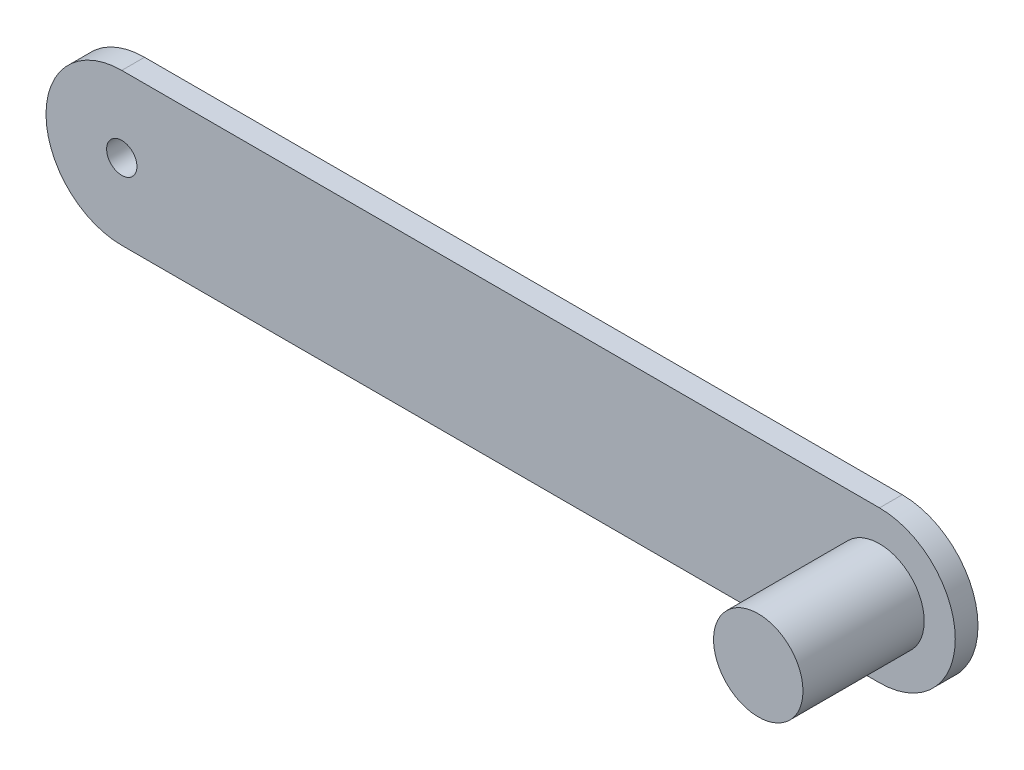
SolidWorks part; units mm, degrees
ref_plane "Front Plane" through (0, 0, 0) normal (0, 0, 1) x (1, 0, 0)
ref_plane "Top Plane" through (0, 0, 0) normal (0, 1, 0) x (1, 0, 0)
ref_plane "Right Plane" through (0, 0, 0) normal (1, 0, 0) x (0, 0, -1)
sketch "Sketch1" plane through (0, 0, 0) normal (0, 0, 1) x (1, 0, 0)
  line L0 (0, 5) -> (50, 5)
  line L6 (0, -5) -> (50, -5)
  arc A2 (0, 5) -> (0, -5) centre (0, 0) ccw
  arc A3 (50, -5) -> (50, 5) centre (50, 0) ccw
  dimension "D1" = 10
  dimension "D2" = 50
extrude "Boss-Extrude4" add sketch "Sketch1" along normal blind 1.5
sketch "Sketch4" plane through (0, 0, 1.5) normal (0, 0, 1) x (1, 0, 0)
  circle A0 centre (0, 0) radius 1
  dimension "D1" = 2
extrude "Cut-Extrude1" cut sketch "Sketch4" against normal through all
sketch "Sketch5" plane through (0, 0, 1.5) normal (0, 0, 1) x (1, 0, 0)
  circle A0 centre (50, 0) radius 2.95
  circle A1 centre (0, 0) radius 1 construction
  dimension "D1" = 5.9
  dimension "D2" = 50
extrude "Boss-Extrude5" add sketch "Sketch5" along normal blind 8
